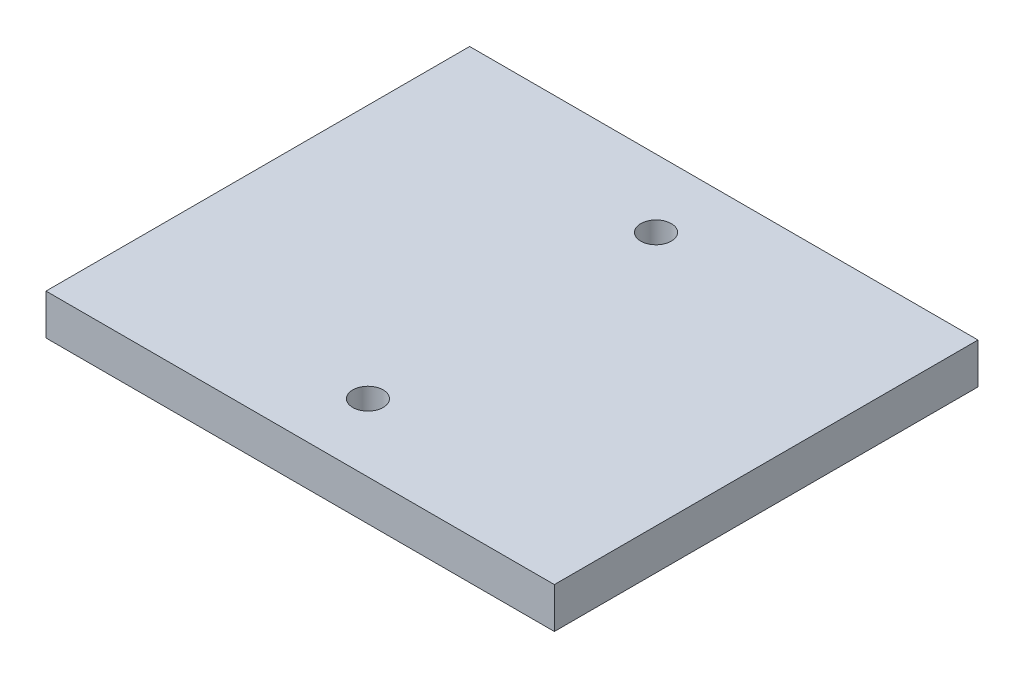
SolidWorks part; units mm, degrees
ref_plane "Front Plane" through (0, 0, 0) normal (0, 0, 1) x (1, 0, 0)
ref_plane "Top Plane" through (0, 0, 0) normal (0, 1, 0) x (1, 0, 0)
ref_plane "Right Plane" through (0, 0, 0) normal (1, 0, 0) x (0, 0, -1)
sketch "Sketch1" plane through (0, 0, 0) normal (0, 1, 0) x (1, 0, 0)
  line L0 (0, -62.5) -> (0, -42.5) construction
  line L1 (-75, -62.5) -> (75, -62.5)
  line L2 (-75, -62.5) -> (-75, 62.5)
  line L3 (-75, 62.5) -> (75, 62.5)
  line L4 (75, -62.5) -> (75, 62.5)
  line L5 (-75, -62.5) -> (75, 62.5) construction
  line L6 (-75, 62.5) -> (75, -62.5) construction
  line L7 (0, 62.5) -> (0, 42.5) construction
  circle A0 centre (0, 42.5) radius 4.5
  circle A1 centre (0, -42.5) radius 4.5
  point P0 (0, 0)
  dimension "D3" = 20
  dimension "D1" = 125
  dimension "D2" = 150
  dimension "D4" = 20
extrude "Boss-Extrude1" add sketch "Sketch1" along normal blind 12
